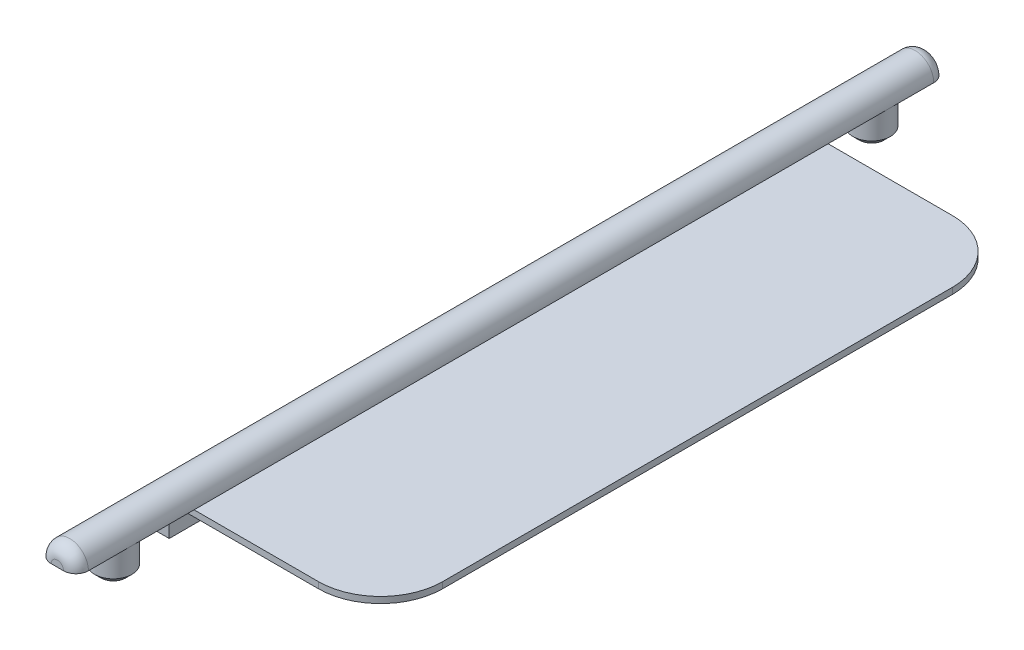
SolidWorks part; units mm, degrees
ref_plane "前视" through (0, 0, 0) normal (0, 0, 1) x (1, 0, 0)
ref_plane "上视" through (0, 0, 0) normal (0, 1, 0) x (1, 0, 0)
ref_plane "右视" through (0, 0, 0) normal (1, 0, 0) x (0, 0, -1)
sketch "草图2" plane through (0, 0, 0) normal (0, 0, 1) x (1, 0, 0)
  line L0 (-3, 0) -> (3, 0)
  line L1 (-3, 0) -> (-3, 1)
  line L2 (3, 0) -> (3, 1)
  arc A2 (3, 1) -> (-3, 1) centre (0, 1) ccw
extrude "凸台-拉伸2" add sketch "草图2" along normal blind 140
sketch "草图4" plane through (0, 0, 0) normal (0, -1, 0) x (1, 0, 0)
  line L1 (-3, 140) -> (3, 140)
  line L2 (-3, 140) -> (-3, 121)
  line L3 (-3, 121) -> (3, 121)
  line L4 (3, 140) -> (3, 121)
  line L5 (3, 0) -> (-3, 0)
  line L6 (3, 0) -> (3, 19)
  line L7 (3, 19) -> (-3, 19)
  line L8 (-3, 0) -> (-3, 19)
extrude "切除-拉伸1" cut sketch "草图4" against normal blind 1
sketch "草图3" plane through (0, 1, 0) normal (0, -1, 0) x (1, 0, 0)
  circle A2 centre (0, 131) radius 3
  circle A3 centre (0, 9) radius 3
extrude "凸台-拉伸4" add sketch "草图3" along normal blind 5
chamfer "倒角2" distance 1 angle 45 2 edges at (0, -4, 128) (0, -4, 6)
fillet "圆角2" radius 2 2 edges at (0, 4, 0) (0, 4, 140)
sketch "草图6" plane through (3, 0, 0) normal (1, 0, 0) x (0, 0, -1)
  line L1 (-121, 1) -> (-19, 1)
  line L2 (-121, 1) -> (-121, 0)
  line L3 (-121, 0) -> (-19, 0)
  line L4 (-19, 1) -> (-19, 0)
extrude "凸台-拉伸5" add sketch "草图6" along normal blind 30
fillet "圆角3" radius 10 2 edges at (33, 0.5, 19) (33, 0.5, 121)
sketch "草图7" plane through (0, 0, 0) normal (0, -1, 0) x (1, 0, 0)
  line L0 (-3, 121) -> (23, 121) construction
  line L1 (-3, 19) -> (-1, 19)
  line L2 (-3, 19) -> (-3, 121)
  line L3 (-3, 121) -> (-1, 121)
  line L4 (-1, 19) -> (-1, 121)
extrude "凸台-拉伸6" add sketch "草图7" along normal blind 5
